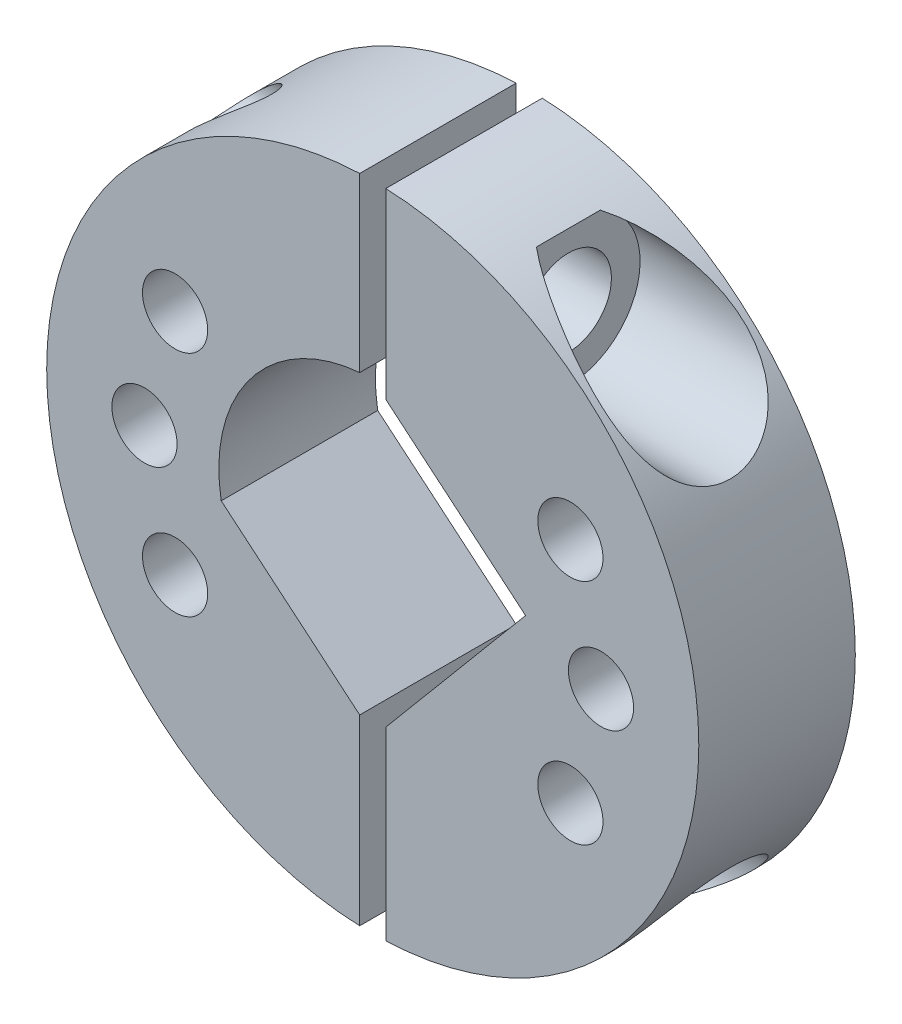
SolidWorks part; units mm, degrees
material "ABS"
ref_plane "정면" through (0, 0, 0) normal (0, 0, 1) x (1, 0, 0)
ref_plane "윗면" through (0, 0, 0) normal (0, 1, 0) x (1, 0, 0)
ref_plane "우측면" through (0, 0, 0) normal (1, 0, 0) x (0, 0, -1)
sketch "스케치7" plane through (0, 0, 0) normal (0, 0, 1) x (1, 0, 0)
  line L0 (11.7158, 1.9832) -> (0.0813, -11.8822)
  line L1 (11.7158, 1.9832) -> (0.0166, 11.8)
  line L2 (0.0813, -11.8822) -> (-11.6178, -2.0654)
  line L3 (0.0166, 11.8) -> (-11.6178, -2.0654) construction
  line L5 (0, 0) -> (-9.0393, 7.5849) construction
  line L6 (0, 11.8) -> (0, 25) construction
  arc A0 (-11.6178, -2.0654) -> (0.0166, 11.8) centre (0, 0) cw
  circle A1 centre (0, 0) radius 25
  circle A2 centre (0, 0) radius 11.8 construction
  dimension "D3" = 11.8
  dimension "D5" = 50
  dimension "D2" = 18.1
  dimension "D4" = 50
  dimension "D1" = 19.5
extrude "보스-돌출1" add sketch "스케치7" along normal mid plane 12 contours A1 | L0 L2 A0 L1
hole_wizard "M6x1.0 나사 구멍1" positions "스케치17" profile "스케치18" tap size "M6x1.0" standard "Ansi Metric"
sketch "스케치17" plane through (0, 0, 6) normal (0, 0, 1) x (1, 0, 0)
  circle A0 centre (0, 0) radius 17.5 construction
  circle A2 centre (0, 0) radius 17.5 construction
  point P19 (0, -17.5)
  point P22 (0, 17.5)
  point P26 (17.5, 0)
  point P32 (15.1554, -8.75)
sketch "스케치18" plane through (17.5, 0, 6) normal (1, 0, 0) x (0, -1, 0)
  line L0 (0, 0) -> (0, 12)
  line L1 (0, 12) -> (2.5, 12)
  line L2 (2.5, 12) -> (2.5, 0)
  line L5 (2.5, 0) -> (0, 0)
  line L11 (0, -6.35) -> (0, 107.95) construction
  dimension "관통 탭 드릴 지름" = 5
  dimension "관통 탭 드릴 깊이" = 12
cosmetic thread "구멍 나사산7" parameters "D2"=6
pattern_circular "원형 패턴2" count 12 over 360 about axis through (0, 0, 0) along (0, 0, 1) skipping 2, 3, 4, 8, 9, 10 of "M6x1.0 나사 구멍1"
sketch "스케치19" plane through (0, 0, 0) normal (0, 0, 1) x (1, 0, 0)
  line L0 (0, 25) -> (0, -25) construction
  line L1 (1, 24.98) -> (1, -24.98)
  line L2 (-1, 24.98) -> (-1, -24.98)
  circle A0 centre (0, 0) radius 25 construction
  arc A1 (-1, -24.98) -> (1, -24.98) centre (0, 0) ccw
  arc A2 (1, 24.98) -> (-1, 24.98) centre (0, 0) ccw
  dimension "D1" = 2
extrude "컷-돌출1" cut sketch "스케치19" against normal through all both and the other way through all
ref_plane "평면1" through (15, 0, 0) normal (1, 0, 0) x (0, 0, -1)
hole_wizard "M6 소켓 머리 캡 나사용 카운터보어1" positions "스케치22" profile "스케치23" counterbore size "M6" standard "Ansi Metric" end condition through all
sketch "스케치22" plane through (15, 0, 0) normal (1, 0, 0) x (0, 0, -1)
  line L0 (-6, 0) -> (6, 0) construction
  line L1 (-6, 24.98) -> (-6, -24.98) construction
  line L2 (6, -24.98) -> (6, 24.98) construction
  line L4 (0, 25) -> (0, 11.8) construction
  point P0 (0, 18.4)
  point P2 (0, -18.4)
sketch "스케치23" plane through (15, 18.4, 0) normal (0, 1, 0) x (0, 0, -1)
  line L0 (0, 0) -> (0, 40)
  line L1 (0, 40) -> (3.3, 40)
  line L3 (3.3, 40) -> (3.3, 6)
  line L4 (3.3, 6) -> (5.5, 6)
  line L5 (5.5, 6) -> (5.5, 0)
  line L7 (5.5, 0) -> (0, 0)
  line L11 (0, -6.35) -> (0, 107.95) construction
  dimension "관통 구멍 지름" = 6.6
  dimension "관통 구멍 깊이" = 40
  dimension "카운터보어 지름" = 11
  dimension "카운터보어 깊이" = 6
hole_wizard "M6x1.0 나사 구멍3" positions "스케치28" profile "스케치29" tap size "M6x1.0" standard "Ansi Metric" end condition through all
sketch "스케치28" plane through (15, 0, 0) normal (1, 0, 0) x (0, 0, -1)
  point P0 (0, 18.4)
  point P3 (0, -18.4)
sketch "스케치29" plane through (15, 18.4, 0) normal (0, 1, 0) x (0, 0, -1)
  line L0 (0, 0) -> (0, 40)
  line L1 (0, 40) -> (2.5, 40)
  line L2 (2.5, 40) -> (2.5, 0)
  line L5 (2.5, 0) -> (0, 0)
  line L11 (0, -6.35) -> (0, 107.95) construction
  dimension "관통 탭 드릴 지름" = 5
  dimension "관통 탭 드릴 깊이" = 40
cosmetic thread "구멍 나사산8" parameters "D2"=6
cosmetic thread "구멍 나사산9" parameters "D2"=6
sketch "스케치30" plane through (15, 0, 0) normal (1, 0, 0) x (0, 0, -1)
  circle A0 centre (0, 18.4) radius 5.5
  arc A1 (-5.2621, 20) -> (5.2621, 20) centre (0, 18.4) ccw construction
  circle A2 centre (0, -18.4) radius 5.5
  arc A4 (5.2621, -20) -> (-5.2621, -20) centre (0, -18.4) ccw construction
extrude "컷-돌출2" cut sketch "스케치30" along normal through all
